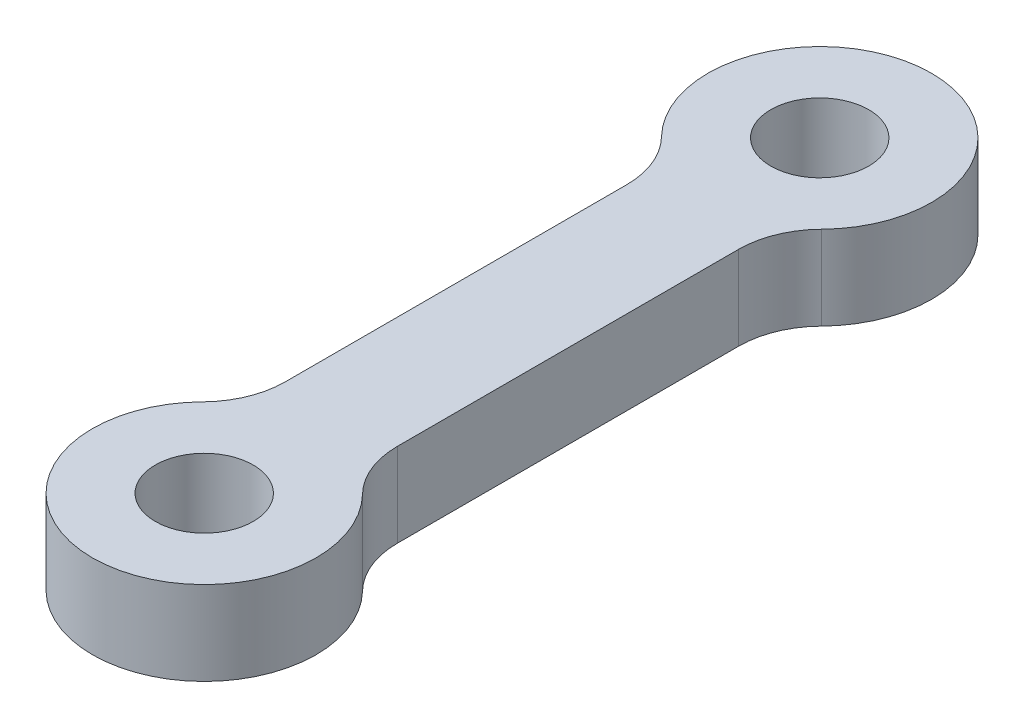
SolidWorks part; units mm, degrees
ref_plane "정면" through (0, 0, 0) normal (0, 0, 1) x (1, 0, 0)
ref_plane "윗면" through (0, 0, 0) normal (0, 1, 0) x (1, 0, 0)
ref_plane "우측면" through (0, 0, 0) normal (1, 0, 0) x (0, 0, -1)
sketch "스케치1" plane through (0, 0, 0) normal (0, 1, 0) x (1, 0, 0)
  line L0 (0, 0) -> (0, 22) construction
  circle A0 centre (0, 0) radius 4
  circle A1 centre (0, 22) radius 4
  dimension "D2" = 22
  dimension "D1" = 8
extrude "보스-돌출1" add sketch "스케치1" along normal blind 3
sketch "스케치2" plane through (0, 3, 0) normal (0, 1, 0) x (1, 0, 0)
  line L0 (0, 0) -> (0, 22) construction
  line L2 (-2, 0) -> (2, 0)
  line L3 (-2, 0) -> (-2, 22)
  line L4 (-2, 22) -> (2, 22)
  line L5 (2, 0) -> (2, 22)
  line L6 (-2, 0) -> (2, 22) construction
  line L7 (-2, 22) -> (2, 0) construction
  point P4 (0, 11)
  dimension "D1" = 4
extrude "보스-돌출2" add sketch "스케치2" against normal blind 3
fillet "필렛1" radius 3 4 edges at (2, 1.5, -3.4641) (-2, 1.5, -3.4641) (-2, 1.5, -18.5359) (2, 1.5, -18.5359)
sketch "스케치3" plane through (0, 3, 0) normal (0, 1, 0) x (1, 0, 0)
  circle A0 centre (0, 22) radius 1.75
  circle A1 centre (0, 0) radius 1.75
  dimension "D1" = 3.5
extrude "컷-돌출1" cut sketch "스케치3" against normal blind 3
